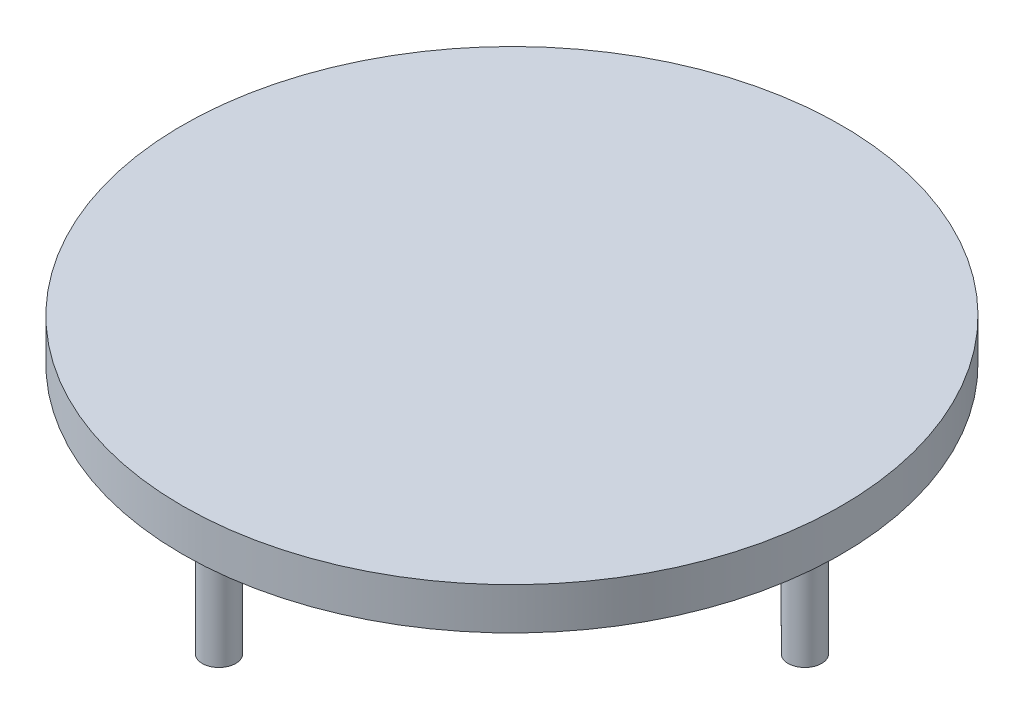
SolidWorks part; units mm, degrees
ref_plane "Front Plane" through (0, 0, 0) normal (0, 0, 1) x (1, 0, 0)
ref_plane "Top Plane" through (0, 0, 0) normal (0, 1, 0) x (1, 0, 0)
ref_plane "Right Plane" through (0, 0, 0) normal (1, 0, 0) x (0, 0, -1)
sketch "Sketch7" plane through (0, 0, 0) normal (0, 1, 0) x (1, 0, 0)
  circle A0 centre (0, 0) radius 15.75
  dimension "D1" = 31.5
extrude "Boss-Extrude5" add sketch "Sketch7" along normal blind 2
sketch "Sketch8" plane through (0, 0, 0) normal (0, -1, 0) x (1, 0, 0)
  circle A0 centre (0, 14) radius 0.8
  circle A1 centre (14, 0) radius 0.8
  circle A2 centre (0, -14) radius 0.8
  circle A3 centre (-14, 0) radius 0.8
  point P12 (0, 0)
  dimension "D1" = 1.6
  dimension "D2" = 14
  dimension "D3" = 4
extrude "Boss-Extrude6" add sketch "Sketch8" along normal blind 5
